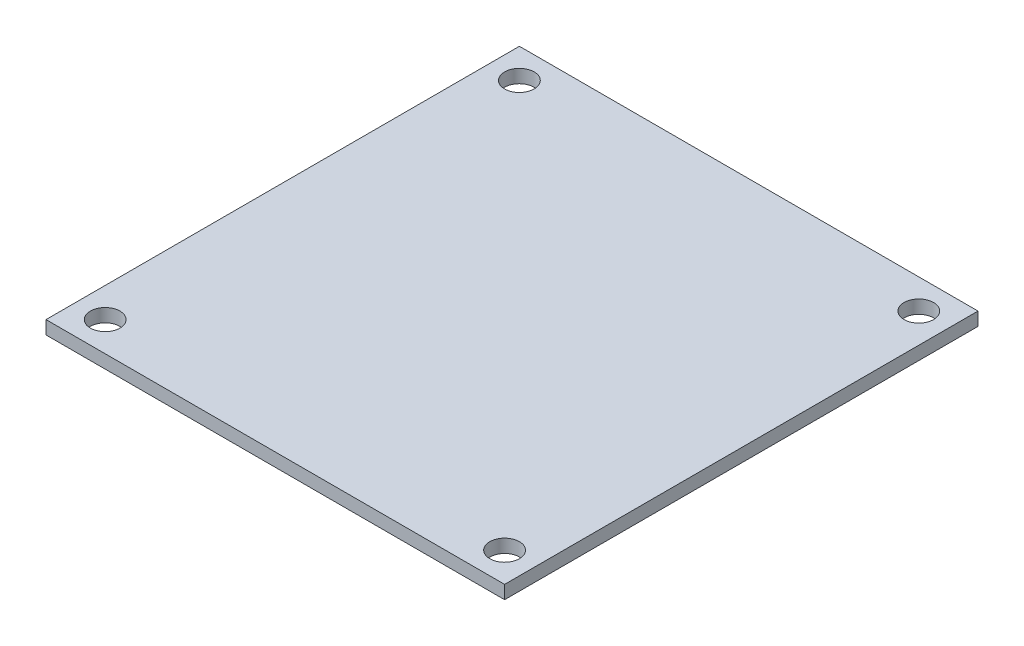
SolidWorks part; units mm, degrees
ref_plane "Front Plane" through (0, 0, 0) normal (0, 0, 1) x (1, 0, 0)
ref_plane "Top Plane" through (0, 0, 0) normal (0, 1, 0) x (1, 0, 0)
ref_plane "Right Plane" through (0, 0, 0) normal (1, 0, 0) x (0, 0, -1)
sketch "Sketch1" plane through (0, 0, 0) normal (0, 1, 0) x (1, 0, 0)
  line L1 (0, 0) -> (31, 0)
  line L2 (0, 0) -> (0, 32)
  line L3 (0, 32) -> (31, 32)
  line L4 (31, 0) -> (31, 32)
  dimension "D1" = 31
  dimension "D2" = 32
extrude "Boss-Extrude1" add sketch "Sketch1" along normal blind 0.9
sketch "Sketch2" plane through (0, 0.9, 0) normal (0, 1, 0) x (1, 0, 0)
  line L0 (15.5, 32) -> (15.5, 0) construction
  line L1 (31, 32) -> (0, 32) construction
  line L2 (0, 0) -> (31, 0) construction
  line L4 (2, 30) -> (29, 30) construction
  line L5 (2, 30) -> (2, 2) construction
  line L6 (2, 2) -> (29, 2) construction
  line L7 (29, 30) -> (29, 2) construction
  line L8 (2, 30) -> (29, 2) construction
  line L9 (2, 2) -> (29, 30) construction
  circle A0 centre (2, 30) radius 1
  circle A1 centre (29, 30) radius 1
  circle A2 centre (29, 2) radius 1
  circle A3 centre (2, 2) radius 1
  point P6 (15.5, 16)
  dimension "D3" = 2
  dimension "D1" = 27
  dimension "D2" = 28
extrude "Cut-Extrude1" cut sketch "Sketch2" against normal through all
